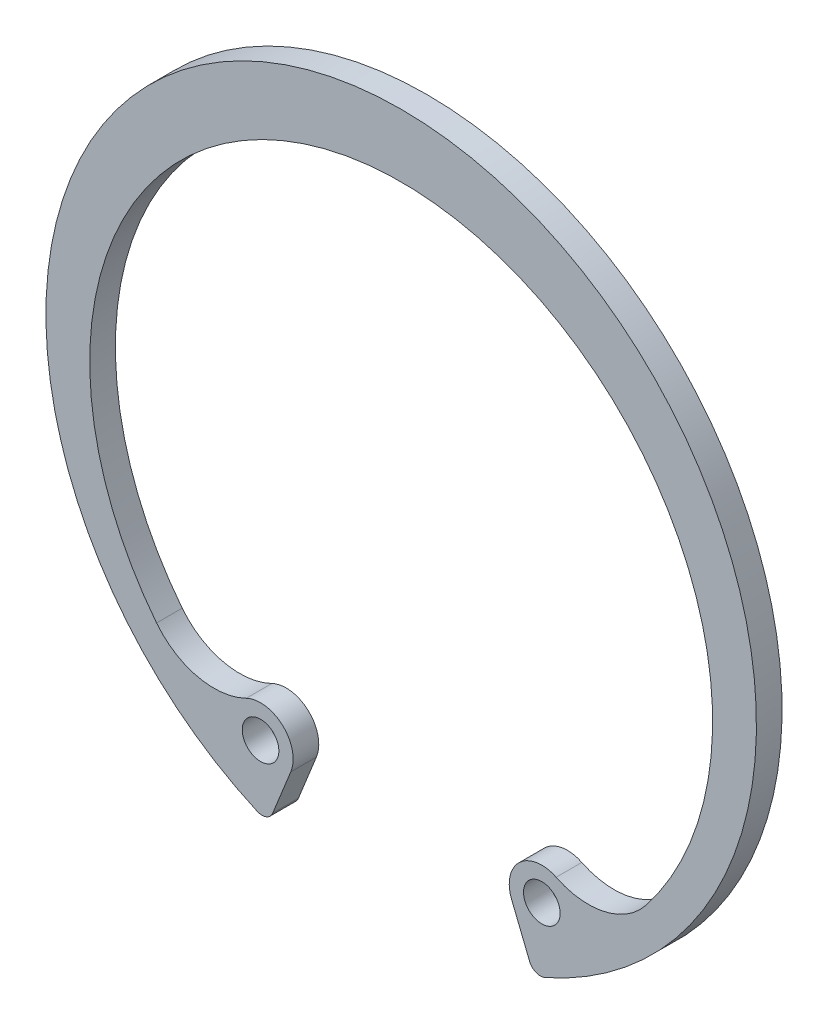
SolidWorks part; units mm, degrees
ref_plane "Front Plane" through (0, 0, 0) normal (0, 0, 1) x (1, 0, 0)
ref_plane "Top Plane" through (0, 0, 0) normal (0, 1, 0) x (1, 0, 0)
ref_plane "Right Plane" through (0, 0, 0) normal (1, 0, 0) x (0, 0, -1)
sketch "Sketch1" plane through (0, 0, 0) normal (0, 0, 1) x (1, 0, 0)
  line L0 (0, 24.25) -> (0, 19.95) construction
  line L1 (-24.25, 0) -> (-22.1, 0) construction
  line L2 (0, 0) -> (0, -24.25) construction
  line L3 (-6.75, -16.7404) -> (-9.0686, -22.4905) construction
  line L4 (-6.75, -16.7404) -> (-9.25, -16.7404) construction
  circle A0 centre (0, 0) radius 23.75 construction
  circle A1 centre (0, 0) radius 24.25 construction
  circle A2 centre (0, 0) radius 22.5 construction
  dimension "Ring OD" = 48.5
  dimension "For ID" = 45
  dimension "Maximum Section" = 4.3
  dimension "Minimum Section" = 2.15
  dimension "Gap Width" = 13.5
  dimension "Lug Height" = 6.2
  dimension "Hole Diameter" = 2.5
sketch "Sketch2" plane through (0, 0, 0) normal (1, 0, 0) x (0, 0, -1)
  line L0 (-0.925, 24.25) -> (0.925, 24.25) construction
  line L1 (-0.875, -24.25) -> (0.875, -24.25) construction
  point P3 (0, 24.25)
  point P7 (0, -24.25)
  point P8 (-0.875, -24.25)
  point P10 (0.875, -24.25)
  point P11 (-0.925, 24.25)
  point P12 (0.925, 24.25)
  dimension "For Groove Width" = 1.85
  dimension "Ring Thickness" = 1.75
sketch "Sketch3" plane through (0, 0, 0) normal (0, 0, 1) x (1, 0, 0)
  line L0 (-9.0686, -22.4905) -> (-6.791, -16.8421) construction
  line L1 (-6.791, -16.8421) -> (-10.0613, -15.0841) construction
  line L2 (0, 0) -> (-8.5463, -15.8985) construction
  line L3 (-16.6968, -14.4678) -> (0, 0) construction
  line L4 (0, 0) -> (0, -24.25) construction
  line L5 (-10.0613, -15.0841) -> (0, 0) construction
  line L6 (-8.5463, -15.8985) -> (-9.5998, -17.8583) construction
  line L7 (-9.5998, -17.8583) -> (-10.6533, -19.8181) construction
  line L8 (0, 24.25) -> (0, 19.95) construction
  line L11 (-7.5363, -18.6904) -> (-9.0686, -22.4905)
  line L12 (0, 0) -> (0, -24.25) construction
  line L13 (7.5363, -18.6904) -> (9.0686, -22.4905)
  line L14 (-6.75, -16.7404) -> (-9.0686, -22.4905) construction
  line L15 (-8.5463, -15.8985) -> (-11.4819, -21.3595) construction
  arc A0 (-9.0686, -22.4905) -> (9.0686, -22.4905) centre (0, 0) cw
  circle A1 centre (0, 0) radius 24.25 construction
  arc A2 (-16.6968, -14.4678) -> (16.6968, -14.4678) centre (0, -1.3089) cw
  circle A4 centre (-9.5998, -17.8583) radius 1.25
  circle A5 centre (0, 0) radius 22.1 construction
  circle A7 centre (9.5998, -17.8583) radius 1.25
  circle A8 centre (0, 0) radius 22.5 construction
  arc A9 (-10.5791, -15.8604) -> (-7.5363, -18.6904) centre (-9.5998, -17.8583) cw
  arc A10 (-16.6968, -14.4678) -> (-10.5791, -15.8604) centre (-12.7761, -11.3778) ccw
  arc A11 (10.5791, -15.8604) -> (7.5363, -18.6904) centre (9.5998, -17.8583) ccw
  arc A12 (16.6968, -14.4678) -> (10.5791, -15.8604) centre (12.7761, -11.3778) cw
  point P3 (0, -24.25)
  dimension "D1" = 2.5
  dimension "D2" = 6.2
  dimension "D3" = 10.075
extrude "Boss-Extrude1" add sketch "Sketch3" against normal up to vertex (0.875 mm away) and the other way up to vertex (0.875 mm away) up to point (0, -24.25, -0.875) other way up to point (0, -24.25, 0.875)
fillet "Fillet1" radius 0.7937 2 edges at (9.0686, -22.4905, 0) (-9.0686, -22.4905, 0)
equation "\"D1@Sketch3\"=\"Hole Diameter@Sketch1\""
equation "\"Minimum Section@Sketch1\"=\"Maximum Section@Sketch1\"*.5"
equation "\"Gap Width@Sketch1\"=\"For ID@Sketch1\"*.3"
equation "\"D2@Sketch3\"=\"Lug Height@Sketch1\""
equation "\"D3@Sketch3\"=\"Lug Height@Sketch1\"*1.625"
